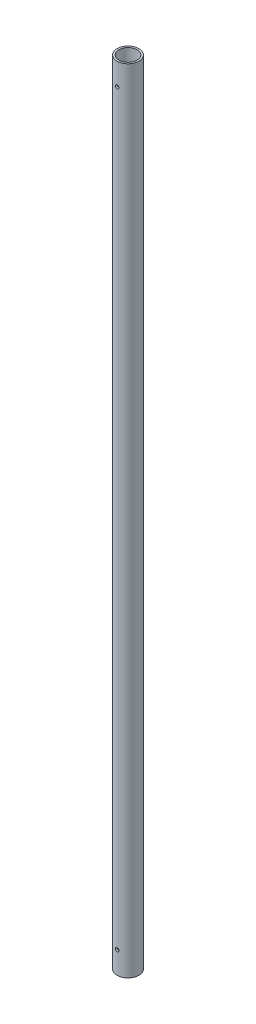
SolidWorks part; units mm, degrees
material "6061 Alloy"
ref_plane "Front Plane" through (0, 0, 0) normal (0, 0, 1) x (1, 0, 0)
ref_plane "Top Plane" through (0, 0, 0) normal (0, 1, 0) x (1, 0, 0)
ref_plane "Right Plane" through (0, 0, 0) normal (1, 0, 0) x (0, 0, -1)
sketch "Sketch1" plane through (0, 0, 0) normal (0, 1, 0) x (1, 0, 0)
  circle A0 centre (0, 0) radius 21.082
  circle A1 centre (0, 0) radius 17.526
  dimension "D1" = 42.164
  dimension "D2" = 35.052
extrude "Boss-Extrude1" add sketch "Sketch1" along normal blind 1530.35
sketch "Sketch2" plane through (0, 0, 0) normal (0, 0, 1) x (1, 0, 0)
  line L0 (-21.082, 0) -> (21.082, 0) construction
  line L1 (17.526, 1530.35) -> (-17.526, 1530.35) construction
  point P0 (0, 1487.3783)
  point P1 (0, 42.9717)
  dimension "D1" = 42.9717
  dimension "D2" = 42.9717
hole_wizard "17/64 (0.26563) Diameter Hole1" positions "Sketch3" profile "Sketch4" hole size "17/64" standard "ANSI Inch"
sketch "Sketch3" plane through (0, 0, 0) normal (0, 0, 1) x (1, 0, 0)
  point P0 (0, 42.9717)
  point P3 (0, 1487.3783)
sketch "Sketch4" plane through (0, 42.9717, 0) normal (1, 0, 0) x (0, 1, 0)
  line L0 (0, 0) -> (0, 21.082)
  line L1 (0, 21.082) -> (3.3735, 21.082)
  line L2 (3.3735, 21.082) -> (3.3735, 0)
  line L5 (3.3735, 0) -> (0, 0)
  line L11 (0, -6.35) -> (0, 107.95) construction
  dimension "Thru Hole Dia." = 6.747
  dimension "Thru Hole Depth" = 21.082
hole_wizard "17/64 (0.26563) Diameter Hole2" positions "Sketch5" profile "Sketch6" hole size "17/64" standard "ANSI Inch" end condition through all
sketch "Sketch5" plane through (0, 0, 0) normal (0, 0, 1) x (1, 0, 0)
  point P0 (0, 1487.3783)
  point P3 (0, 42.9717)
sketch "Sketch6" plane through (0, 1487.3783, 0) normal (1, 0, 0) x (0, -1, 0)
  line L0 (0, 0) -> (0, 21.082)
  line L1 (0, 21.082) -> (3.3735, 21.082)
  line L2 (3.3735, 21.082) -> (3.3735, 0)
  line L5 (3.3735, 0) -> (0, 0)
  line L11 (0, -6.35) -> (0, 107.95) construction
  dimension "Thru Hole Dia." = 6.747
  dimension "Thru Hole Depth" = 21.082
